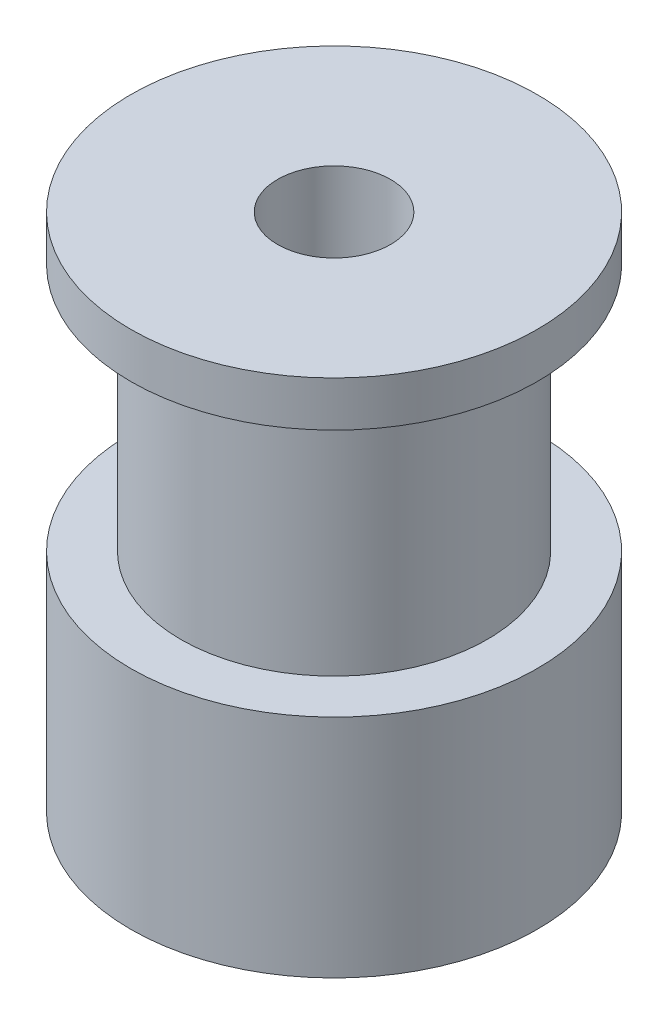
SolidWorks part; units mm, degrees
material "AISI 304"
ref_plane "前视基准面" through (0, 0, 0) normal (0, 0, 1) x (1, 0, 0)
ref_plane "上视基准面" through (0, 0, 0) normal (0, 1, 0) x (1, 0, 0)
ref_plane "右视基准面" through (0, 0, 0) normal (1, 0, 0) x (0, 0, -1)
other "Configuration Table"
sketch "草图1" plane through (0, 0, 0) normal (0, 1, 0) x (1, 0, 0)
  circle A0 centre (0, 0) radius 9
  dimension "D1" = 18
extrude "凸台-拉伸1" add sketch "草图1" along normal blind 8
sketch "草图2" plane through (0, 8, 0) normal (0, 1, 0) x (1, 0, 0)
  circle A0 centre (0, 0) radius 9
  dimension "D1" = 18
extrude "凸台-拉伸2" add sketch "草图2" along normal blind 2
sketch "草图3" plane through (0, 10, 0) normal (0, 1, 0) x (1, 0, 0)
  circle A0 centre (0, 0) radius 6.78
  dimension "D1" = 13.56
extrude "凸台-拉伸3" add sketch "草图3" along normal blind 11
sketch "草图4" plane through (0, 21, 0) normal (0, 1, 0) x (1, 0, 0)
  circle A0 centre (0, 0) radius 9
extrude "凸台-拉伸4" add sketch "草图4" along normal blind 2
sketch "草图5" plane through (0, 23, 0) normal (0, 1, 0) x (1, 0, 0)
  circle A0 centre (0, 0) radius 2.5
  dimension "D1" = 5
extrude "切除-拉伸1" cut sketch "草图5" against normal blind 31
